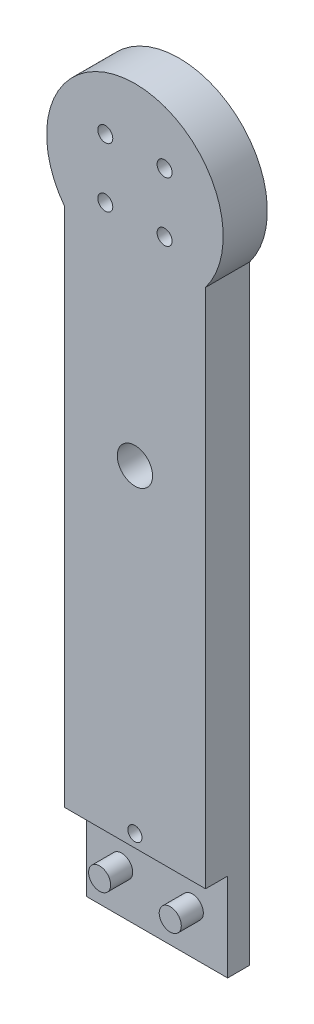
SolidWorks part; units mm, degrees
ref_plane "Plan de face" through (0, 0, 0) normal (0, 0, 1) x (1, 0, 0)
ref_plane "Plan de dessus" through (0, 0, 0) normal (0, 1, 0) x (1, 0, 0)
ref_plane "Plan de droite" through (0, 0, 0) normal (1, 0, 0) x (0, 0, -1)
sketch "Esquisse1" plane through (0, 0, 0) normal (0, 0, 1) x (1, 0, 0)
  line L1 (16, 0) -> (-16, 0)
  line L2 (16, 0) -> (16, 130)
  line L3 (16, 130) -> (-16, 130)
  line L4 (-16, 0) -> (-16, 130)
  circle A0 centre (0, 130) radius 20
  dimension "D3" = 40
  dimension "D1" = 130
  dimension "D2" = 32
extrude "Boss.-Extru.1" add sketch "Esquisse1" along normal blind 10 contours L4 A0 L2 L3 | L2 A0 L4 L3 | A0 L4 L1 L2
sketch "Esquisse3" plane through (0, 0, 0) normal (0, -1, 0) x (1, 0, 0)
  line L0 (-16, 10) -> (-16, 0) construction
  line L1 (-16, 5) -> (16, 5)
  line L2 (-16, 5) -> (-16, 0)
  line L3 (-16, 0) -> (16, 0)
  line L4 (16, 5) -> (16, 0)
  dimension "D1" = 5
extrude "Boss.-Extru.2" add sketch "Esquisse3" along normal blind 20
sketch "Esquisse4" plane through (0, 0, 5) normal (0, 0, 1) x (1, 0, 0)
  line L0 (0, 0) -> (0, -20) construction
  line L1 (16, 0) -> (-16, 0) construction
  line L2 (16, -20) -> (-16, -20) construction
  line L3 (-16, -10) -> (0, -10) construction
  line L4 (-16, -20) -> (-16, 0) construction
  circle A0 centre (-8, -10) radius 2.5
  circle A1 centre (8, -10) radius 2.5
  dimension "D1" = 5
extrude "Boss.-Extru.3" add sketch "Esquisse4" along normal blind 5
sketch "Esquisse6" plane through (0, 0, 10) normal (0, 0, 1) x (1, 0, 0)
  line L0 (0, 130) -> (0, 139.5) construction
  line L1 (-6.7175, 136.7175) -> (0, 130) construction
  line L2 (0, 0) -> (0, 150) construction
  circle A0 centre (0, 130) radius 9.5 construction
  arc A1 (16, 118) -> (-16, 118) centre (0, 130) ccw construction
  circle A2 centre (-6.7175, 136.7175) radius 1.7
  circle A3 centre (6.7175, 136.7175) radius 1.7
  circle A4 centre (6.7175, 123.2825) radius 1.7
  circle A5 centre (-6.7175, 123.2825) radius 1.7
  circle A6 centre (0, 75) radius 4
  circle A7 centre (0, 2.83) radius 1.6
  point P17 (0, 130)
  dimension "D1" = 19
  dimension "D2" = 3.4
  dimension "D5" = 8
  dimension "D6" = 3.2
  dimension "D3" = 45
  dimension "D7" = 2.83
  dimension "D4" = 4
extrude "Enlèv. mat.-Extru.1" cut sketch "Esquisse6" against normal through all
